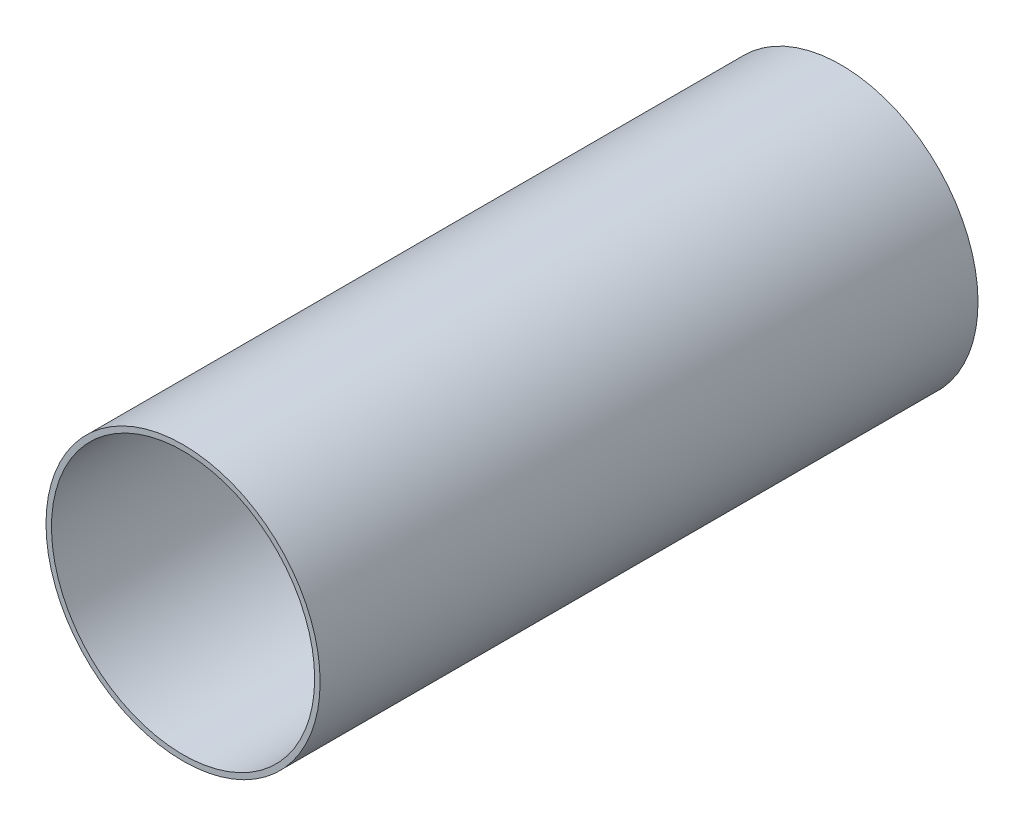
SolidWorks part; units mm, degrees
ref_plane "Plan de face" through (0, 0, 0) normal (0, 0, 1) x (1, 0, 0)
ref_plane "Plan de dessus" through (0, 0, 0) normal (0, 1, 0) x (1, 0, 0)
ref_plane "Plan de droite" through (0, 0, 0) normal (1, 0, 0) x (0, 0, -1)
sketch "Esquisse1" plane through (0, 0, 0) normal (0, 0, 1) x (1, 0, 0)
  circle A0 centre (0, 0) radius 25
  dimension "D1" = 50
extrude "Extru.-Mince1" add sketch "Esquisse1" along normal blind 120 thin thin type one direction reverse wall 1
sketch "Esquisse2" plane through (0, 0, 0) normal (0, 1, 0) x (1, 0, 0)
  line L0 (0, 0) -> (0, -40) construction
  line L1 (24, 0) -> (-24, 0) construction
  line L2 (-15, 0) -> (15, 0)
  line L3 (-15, 0) -> (-15, -40)
  line L4 (-15, -40) -> (15, -40)
  line L5 (15, 0) -> (15, -40)
  dimension "D1" = 40
  dimension "D2" = 30
  dimension "D3" = 15
extrude "Enlèv. mat.-Extru.1" cut sketch "Esquisse2" against normal through all
